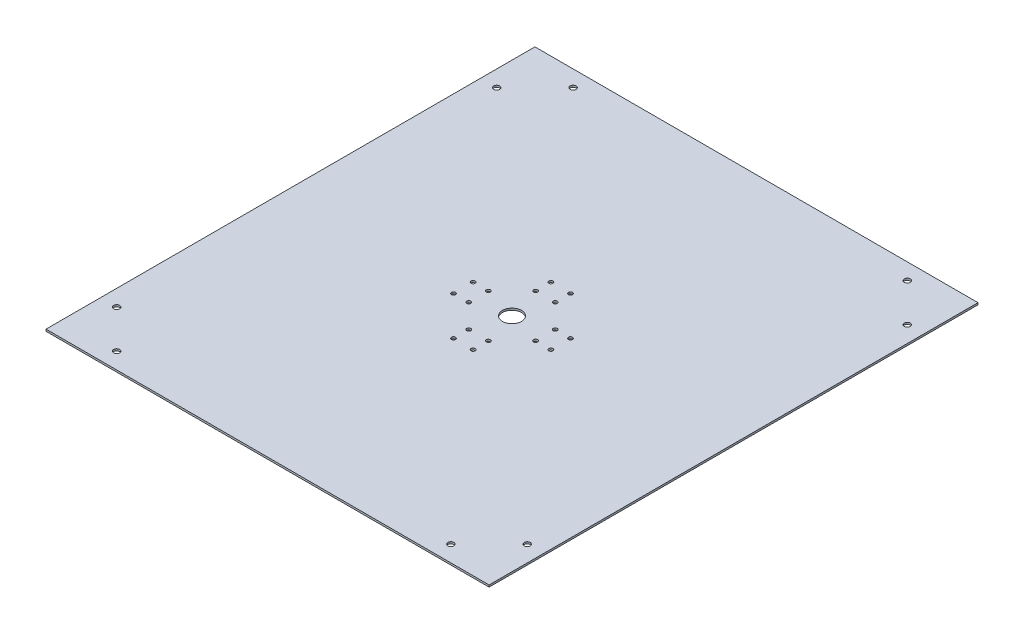
SolidWorks part; units mm, degrees
material "6061 Alloy"
ref_plane "Front Plane" through (0, 0, 0) normal (0, 0, 1) x (1, 0, 0)
ref_plane "Top Plane" through (0, 0, 0) normal (0, 1, 0) x (1, 0, 0)
ref_plane "Right Plane" through (0, 0, 0) normal (1, 0, 0) x (0, 0, -1)
sketch "Sketch1" plane through (0, 0, 0) normal (0, 1, 0) x (1, 0, 0)
  line L1 (-232, -256) -> (232, -256)
  line L2 (-232, -256) -> (-232, 256)
  line L3 (-232, 256) -> (232, 256)
  line L4 (232, -256) -> (232, 256)
  line L5 (-232, -256) -> (232, 256) construction
  line L6 (-232, 256) -> (232, -256) construction
  point P0 (0, 0)
  dimension "D1" = 464
  dimension "D2" = 512
extrude "Boss-Extrude1" add sketch "Sketch1" along normal blind 2
sketch "Sketch2" plane through (0, 2, 0) normal (0, 1, 0) x (1, 0, 0)
  circle A0 centre (0, 0) radius 10
  dimension "D1" = 20
extrude "Cut-Extrude1" cut sketch "Sketch2" against normal blind 10
sketch "Sketch3" plane through (0, 2, 0) normal (0, 1, 0) x (1, 0, 0)
  line L0 (0, 58) -> (0, -58) construction
  line L1 (-58, -58) -> (58, -58) construction
  line L2 (-58, -58) -> (-58, 58) construction
  line L3 (-58, 58) -> (58, 58) construction
  line L4 (58, -58) -> (58, 58) construction
  line L5 (-58, -58) -> (58, 58) construction
  line L6 (-58, 58) -> (58, -58) construction
  line L7 (-58, 0) -> (58, 0) construction
  line L8 (-10.25, 35) -> (0, 35) construction
  line L9 (-10.25, 35) -> (-10.25, 51) construction
  circle A1 centre (-10.25, 51) radius 2.15
  circle A3 centre (-10.25, 35) radius 2.15
  circle A4 centre (10.25, 35) radius 2.15
  circle A5 centre (10.25, 51) radius 2.15
  circle A6 centre (35, 10.25) radius 2.15
  circle A7 centre (51, 10.25) radius 2.15
  circle A8 centre (51, -10.25) radius 2.15
  circle A9 centre (35, -10.25) radius 2.15
  circle A10 centre (10.25, -35) radius 2.15
  circle A11 centre (10.25, -51) radius 2.15
  circle A12 centre (-10.25, -51) radius 2.15
  circle A13 centre (-10.25, -35) radius 2.15
  circle A14 centre (-35, -10.25) radius 2.15
  circle A15 centre (-51, -10.25) radius 2.15
  circle A16 centre (-51, 10.25) radius 2.15
  circle A17 centre (-35, 10.25) radius 2.15
  circle A18 centre (0, 0) radius 36.47 construction
  point P0 (0, 0)
  point P46 (0, 0)
  dimension "D5" = 4.3
  dimension "D7" = 4.3
  dimension "D1" = 116
  dimension "D2" = 116
  dimension "D3" = 10.25
  dimension "D4" = 7
  dimension "D6" = 16
  dimension "D8" = 4
extrude "Cut-Extrude2" cut sketch "Sketch3" against normal blind 10
sketch "Sketch4" plane through (0, 2, 0) normal (0, 1, 0) x (1, 0, 0)
  line L0 (-215, -256) -> (-215, -239) construction
  line L1 (-232, -256) -> (232, -256) construction
  line L2 (-215, -239) -> (-232, -239) construction
  line L3 (-232, 256) -> (-232, -256) construction
  line L4 (0, 0) -> (232, 0) construction
  line L5 (232, -256) -> (232, 256) construction
  line L6 (0, 0) -> (0, 256) construction
  line L7 (232, 256) -> (-232, 256) construction
  circle A0 centre (-215, -199) radius 3.15
  circle A1 centre (-175, -239) radius 3.15
  circle A2 centre (-215, 199) radius 3.15
  circle A3 centre (-175, 239) radius 3.15
  circle A4 centre (175, -239) radius 3.15
  circle A5 centre (215, -199) radius 3.15
  circle A6 centre (215, 199) radius 3.15
  circle A7 centre (175, 239) radius 3.15
  dimension "D3" = 6.3
  dimension "D5" = 6.3
  dimension "D1" = 17
  dimension "D2" = 17
  dimension "D4" = 40
  dimension "D6" = 40
extrude "Cut-Extrude3" cut sketch "Sketch4" against normal blind 10
